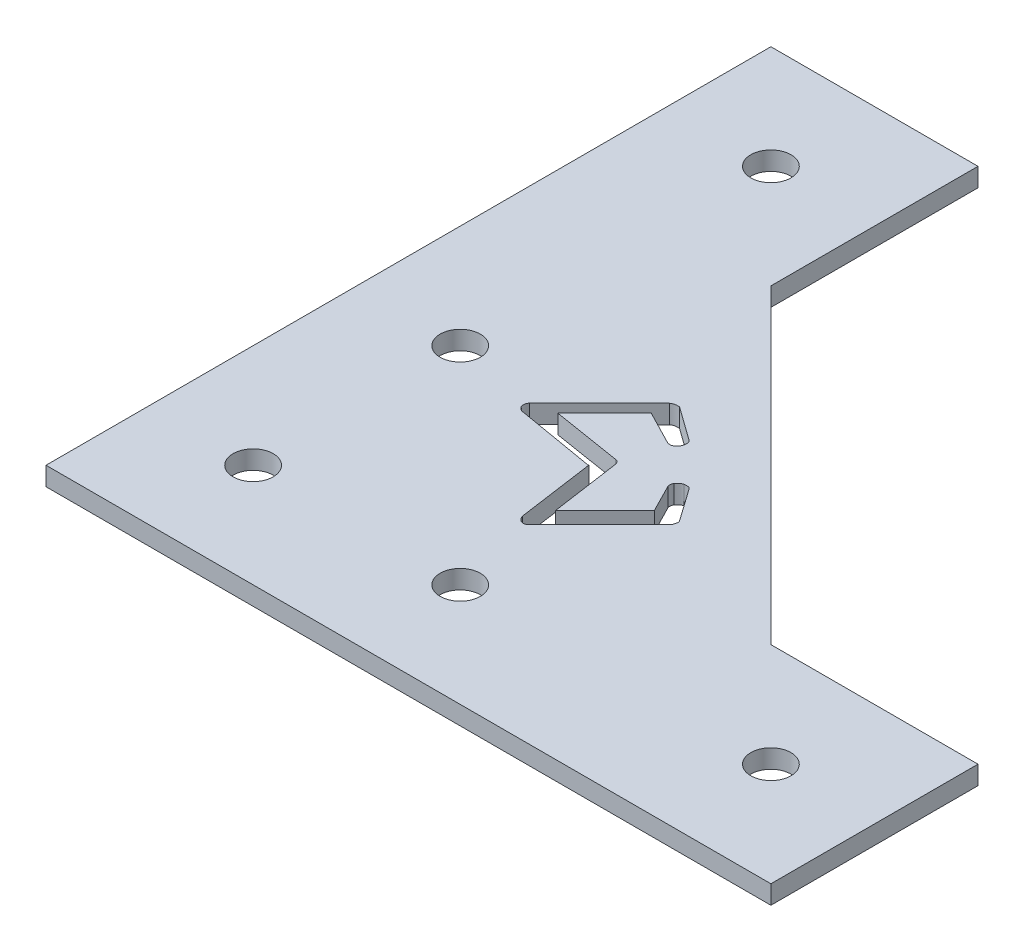
SolidWorks part; units mm, degrees
material "1060 Alloy"
ref_plane "Front Plane" through (0, 0, 0) normal (0, 0, 1) x (1, 0, 0)
ref_plane "Top Plane" through (0, 0, 0) normal (0, 1, 0) x (1, 0, 0)
ref_plane "Right Plane" through (0, 0, 0) normal (1, 0, 0) x (0, 0, -1)
sketch "Sketch1" plane through (0, 0, 0) normal (0, 1, 0) x (1, 0, 0)
  line L0 (25.4, 63.5) -> (63.5, 25.4)
  line L1 (0, 0) -> (88.9, 0)
  line L2 (0, 88.9) -> (0, 0)
  line L8 (63.5, 25.4) -> (88.9, 25.4)
  line L9 (88.9, 0) -> (88.9, 25.4)
  line L12 (0, 88.9) -> (25.4, 88.9)
  line L13 (25.4, 63.5) -> (25.4, 88.9)
  dimension "D2" = 88.9
  dimension "D3" = 25.4
extrude "Boss-Extrude1" add sketch "Sketch1" along normal blind 2.286
sketch "Sketch2" plane through (0, 2.286, 0) normal (0, 1, 0) x (1, 0, 0)
  text T0 "<r45>S</r>" font "SWGrekc" height in points 70
extrude "Cut-Extrude1" cut sketch "Sketch2" against normal through all
sketch "Sketch3" plane through (0, 2.286, 0) normal (0, 1, 0) x (1, 0, 0)
  line L0 (0, 12.7) -> (88.9, 12.7) construction
  line L1 (0, 88.9) -> (0, 0) construction
  line L2 (88.9, 0) -> (88.9, 25.4) construction
  line L3 (12.7, 88.9) -> (12.7, 0) construction
  line L4 (25.4, 88.9) -> (0, 88.9) construction
  line L5 (0, 0) -> (88.9, 0) construction
  circle A0 centre (76.2, 12.7) radius 2.4638
  circle A1 centre (12.7, 12.7) radius 2.4638
  circle A2 centre (12.7, 76.2) radius 2.4638
  circle A3 centre (12.7, 38.1) radius 2.4638
  circle A4 centre (38.1, 12.7) radius 2.4638
  dimension "D1" = 4.9276
  dimension "D2" = 12.7
  dimension "D3" = 12.7
  dimension "D4" = 25.4
  dimension "D5" = 25.4
extrude "Cut-Extrude2" cut sketch "Sketch3" against normal through all
